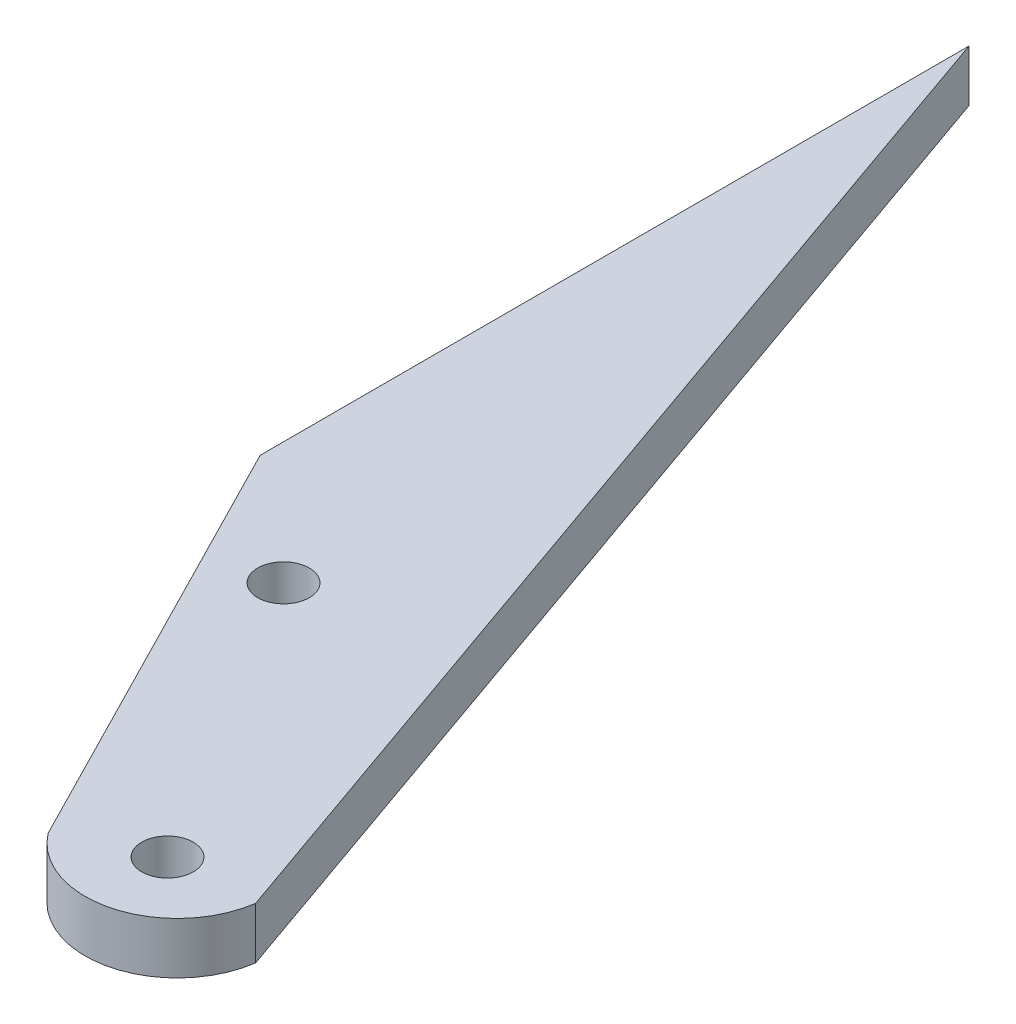
SolidWorks part; units mm, degrees
material "Plain Carbon Steel"
ref_plane "Front Plane" through (0, 0, 0) normal (0, 0, 1) x (1, 0, 0)
ref_plane "Top Plane" through (0, 0, 0) normal (0, 1, 0) x (1, 0, 0)
ref_plane "Right Plane" through (0, 0, 0) normal (1, 0, 0) x (0, 0, -1)
sketch "Sketch1" plane through (0, 0, 0) normal (0, 1, 0) x (1, 0, 0)
  line L0 (-22.4436, 63.9457) -> (-22.4436, 22.7057)
  line L1 (-22.4436, 63.9457) -> (0, 0)
  line L2 (-22.4436, 22.7057) -> (-9.5737, -2.4985)
  line L3 (-22.4436, 22.7057) -> (-15.3365, 16.9587) construction
  line L4 (-15.3365, 16.9587) -> (-4.8979, -0.2299) construction
  arc A0 (-9.5737, -2.4985) -> (0, 0) centre (-5.3082, 0.7483) ccw
  circle A2 centre (-15.3365, 16.9587) radius 1.5
  circle A3 centre (-4.8979, -0.2299) radius 1.5
  dimension "D1" = 67.77
  dimension "D2" = 128.96
  dimension "D8" = 160.23
  dimension "D10" = 3
  dimension "D11" = 3
  dimension "D3" = 41.24
  dimension "D4" = 19.34
  dimension "D5" = 28.3
  dimension "D6" = 152.95
  dimension "D7" = 9.14
  dimension "D9" = 20.11
extrude "Boss-Extrude1" add sketch "Sketch1" along normal blind 3
